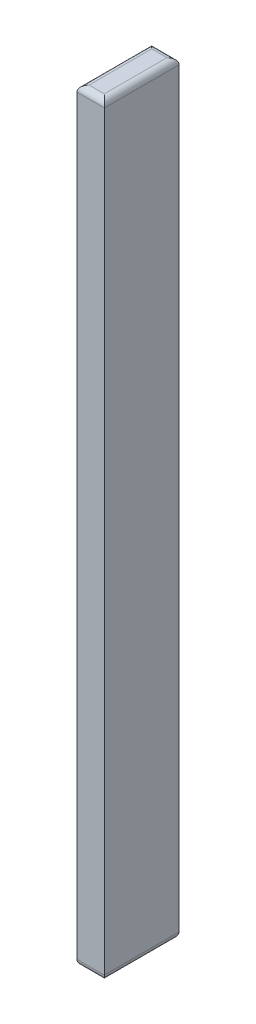
SolidWorks part; units mm, degrees
ref_plane "Front Plane" through (0, 0, 0) normal (0, 0, 1) x (1, 0, 0)
ref_plane "Top Plane" through (0, 0, 0) normal (0, 1, 0) x (1, 0, 0)
ref_plane "Right Plane" through (0, 0, 0) normal (1, 0, 0) x (0, 0, -1)
sketch "Sketch1" plane through (0, 0, 0) normal (0, 1, 0) x (1, 0, 0)
  line L1 (0, 0) -> (9, 0)
  line L2 (0, 0) -> (0, 24.5)
  line L3 (0, 24.5) -> (9, 24.5)
  line L4 (9, 0) -> (9, 24.5)
  dimension "D1" = 24.5
  dimension "D2" = 9
extrude "Boss-Extrude1" add sketch "Sketch1" along normal blind 250
fillet "Fillet1" radius 2 8 edges at (4.5, 0, 0) (9, 0, -12.25) (4.5, 0, -24.5) (0, 0, -12.25) (4.5, 250, -24.5) (9, 250, -12.25) (4.5, 250, 0) (0, 250, -12.25)
